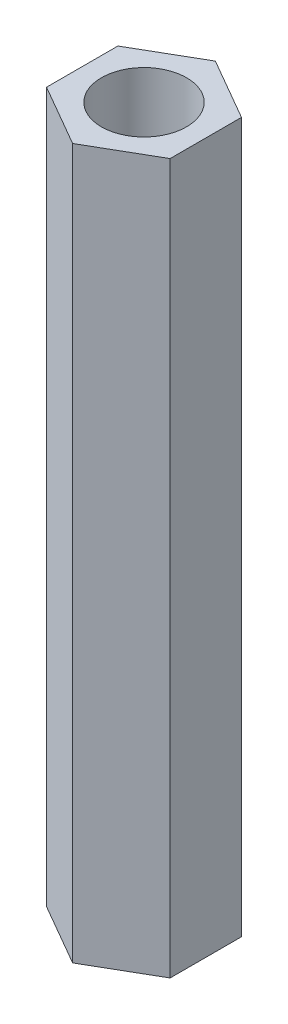
SolidWorks part; units mm, degrees
material "黄铜"
ref_plane "前视基准面" through (0, 0, 0) normal (0, 0, 1) x (1, 0, 0)
ref_plane "上视基准面" through (0, 0, 0) normal (0, 1, 0) x (1, 0, 0)
ref_plane "右视基准面" through (0, 0, 0) normal (1, 0, 0) x (0, 0, -1)
sketch "草图1" plane through (0, 0, 0) normal (0, 1, 0) x (1, 0, 0)
  line L0 (0, 2.5139) -> (-2.1771, 1.257)
  line L1 (-2.1771, 1.257) -> (-2.1771, -1.257)
  line L2 (-2.1771, -1.257) -> (0, -2.5139)
  line L3 (0, -2.5139) -> (2.1771, -1.257)
  line L4 (2.1771, -1.257) -> (2.1771, 1.257)
  line L5 (2.1771, 1.257) -> (0, 2.5139)
  circle A0 centre (0, 0) radius 1.5
extrude "凸台-拉伸1" add sketch "草图1" along normal blind 25
